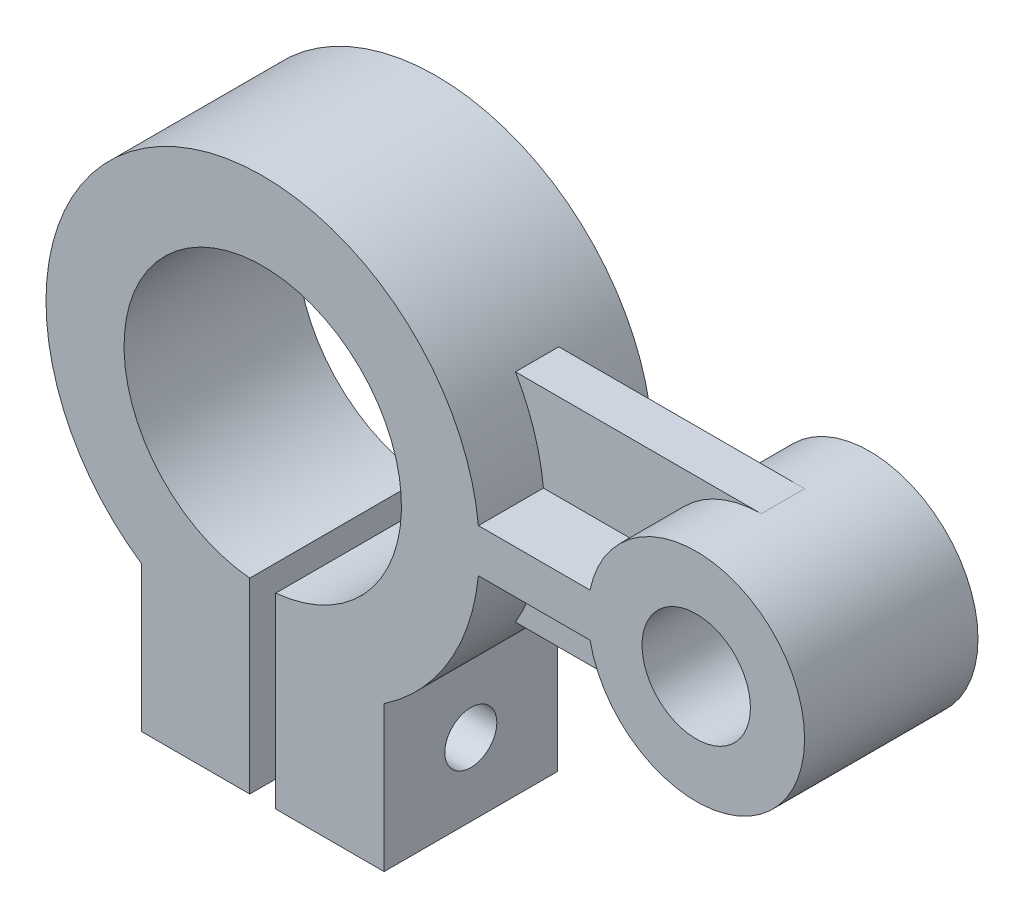
SolidWorks part; units mm, degrees
ref_plane "Front Plane" through (0, 0, 0) normal (0, 0, 1) x (1, 0, 0)
ref_plane "Top Plane" through (0, 0, 0) normal (0, 1, 0) x (1, 0, 0)
ref_plane "Right Plane" through (0, 0, 0) normal (1, 0, 0) x (0, 0, -1)
sketch "Sketch1" plane through (0, 0, 0) normal (0, 0, 1) x (1, 0, 0)
  line L0 (-68.3811, -39.5655) -> (-68.3811, 3.5755)
  line L1 (-15.6317, 40.4345) -> (10.124, 40.4345)
  line L3 (-62.3811, -39.5655) -> (-62.3811, 3.5755)
  line L4 (-68.3811, -39.5655) -> (-93.3811, -39.5655)
  line L5 (-62.3811, -39.5655) -> (-37.3811, -39.5655)
  line L6 (-93.3811, -39.5655) -> (-93.3811, -5.9901)
  line L7 (-37.3811, -39.5655) -> (-37.3811, -5.9901)
  line L9 (-15.6317, 30.4345) -> (10.124, 30.4345)
  arc A0 (-37.3811, -5.9901) -> (-15.6317, 30.4345) centre (-65.3811, 35.4345) ccw
  arc A1 (-62.3811, 3.5755) -> (-68.3811, 3.5755) centre (-65.3811, 35.4345) ccw
  arc A2 (10.124, 30.4345) -> (10.124, 40.4345) centre (34.6189, 35.4345) ccw
  circle A3 centre (34.6189, 35.4345) radius 12.5
  arc A4 (-15.6317, 40.4345) -> (-93.3811, -5.9901) centre (-65.3811, 35.4345) ccw
extrude "Boss-Extrude1" add sketch "Sketch1" along normal mid plane 40
sketch "Sketch2" plane through (-37.3811, 0, 0) normal (1, 0, 0) x (0, 0, -1)
  circle A0 centre (0, -22.7778) radius 6
extrude "Cut-Extrude2" cut sketch "Sketch2" against normal blind 56
ref_plane "Plane1" through (0, 0, 0) normal (0, 0, 1) x (1, 0, 0)
sketch "Sketch7" plane through (0, 0, 0) normal (0, 0, 1) x (1, 0, 0)
  line L0 (34.6189, 60.4345) -> (-22.0798, 60.4345)
  line L1 (34.6189, 10.4345) -> (-22.0798, 10.4345)
  line L8 (-93.3811, -39.5655) -> (-68.3811, -39.5655)
  line L9 (-68.3811, -39.5655) -> (-68.3811, 3.5755)
  line L10 (-62.3811, 3.5755) -> (-62.3811, -39.5655)
  line L11 (-62.3811, -39.5655) -> (-37.3811, -39.5655)
  line L12 (-37.3811, -39.5655) -> (-37.3811, -5.9901)
  line L13 (-15.6317, 30.4345) -> (10.124, 30.4345)
  line L14 (10.124, 40.4345) -> (-15.6317, 40.4345)
  line L15 (-93.3811, -5.9901) -> (-93.3811, -39.5655)
  line L16 (-93.3811, -39.5655) -> (-68.3811, -39.5655)
  line L17 (-68.3811, -39.5655) -> (-68.3811, 3.5755)
  line L18 (-62.3811, 3.5755) -> (-62.3811, -39.5655)
  line L19 (-62.3811, -39.5655) -> (-37.3811, -39.5655)
  line L20 (-37.3811, -39.5655) -> (-37.3811, -5.9901)
  line L21 (-15.6317, 30.4345) -> (10.124, 30.4345)
  line L22 (10.124, 40.4345) -> (-15.6317, 40.4345)
  line L23 (-93.3811, -5.9901) -> (-93.3811, -39.5655)
  arc A4 (-62.3811, 3.5755) -> (-68.3811, 3.5755) centre (-65.3811, 35.4345) ccw
  arc A5 (-37.3811, -5.9901) -> (-15.6317, 30.4345) centre (-65.3811, 35.4345) ccw
  arc A6 (10.124, 30.4345) -> (10.124, 40.4345) centre (34.6189, 35.4345) ccw
  arc A7 (-15.6317, 40.4345) -> (-93.3811, -5.9901) centre (-65.3811, 35.4345) ccw
  arc A8 (-62.3811, 3.5755) -> (-68.3811, 3.5755) centre (-65.3811, 35.4345) ccw
  arc A9 (-37.3811, -5.9901) -> (-15.6317, 30.4345) centre (-65.3811, 35.4345) ccw
  arc A10 (10.124, 30.4345) -> (10.124, 40.4345) centre (34.6189, 35.4345) ccw
  arc A11 (-15.6317, 40.4345) -> (-93.3811, -5.9901) centre (-65.3811, 35.4345) ccw
  dimension "D2" = 50
  dimension "D1" = 0
extrude "Boss-Extrude2" add sketch "Sketch7" along normal blind 5 and the other way blind 5 contours A11 L22 A10 L0 | A10 L21 A9 L1
